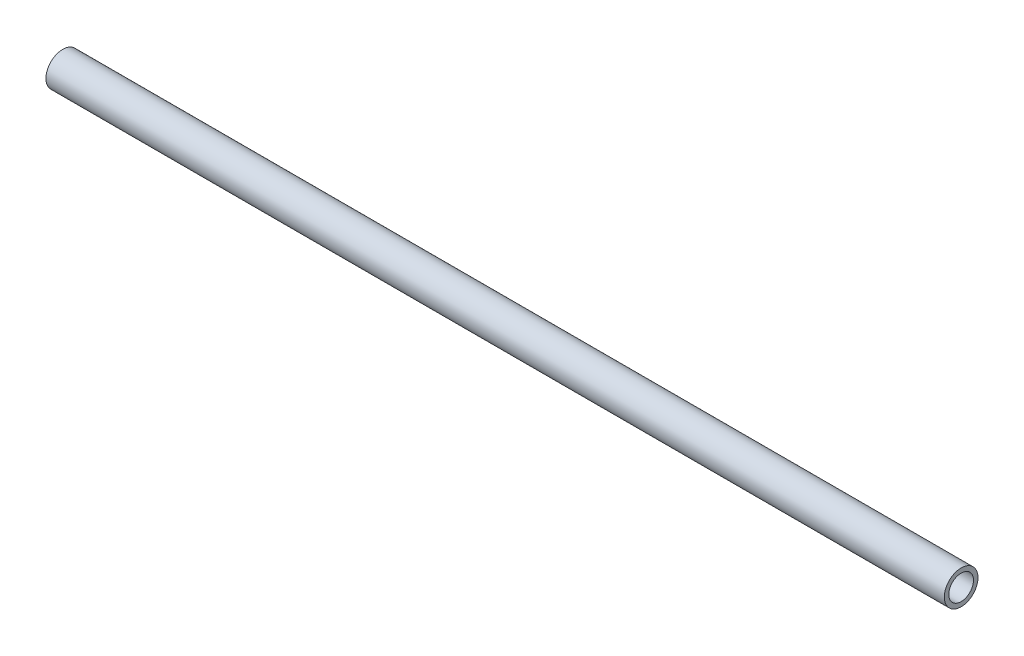
SolidWorks part; units mm, degrees
ref_plane "Front Plane" through (0, 0, 0) normal (0, 0, 1) x (1, 0, 0)
ref_plane "Top Plane" through (0, 0, 0) normal (0, 1, 0) x (1, 0, 0)
ref_plane "Right Plane" through (0, 0, 0) normal (1, 0, 0) x (0, 0, -1)
sketch "Sketch5" plane through (0, 0, 0) normal (0, 0, 1) x (1, 0, 0)
  line L0 (-390.1784, -2.5109) -> (9.8216, -2.5109)
  dimension "D1" = 400
ref_plane "Plane1" through (-390.1784, 0, 0) normal (1, 0, 0) x (0, 0, -1)
sketch "Sketch6" plane through (-390.1784, 0, 0) normal (1, 0, 0) x (0, 0, -1)
  circle A0 centre (0, -1.011) radius 5.5
  circle A1 centre (0, -1.011) radius 7.5
  dimension "D1" = 15
  dimension "D2" = 2
sweep "Sweep1" add profiles "Sketch6" path "Sketch5"
equation "\"4\"= 4"
